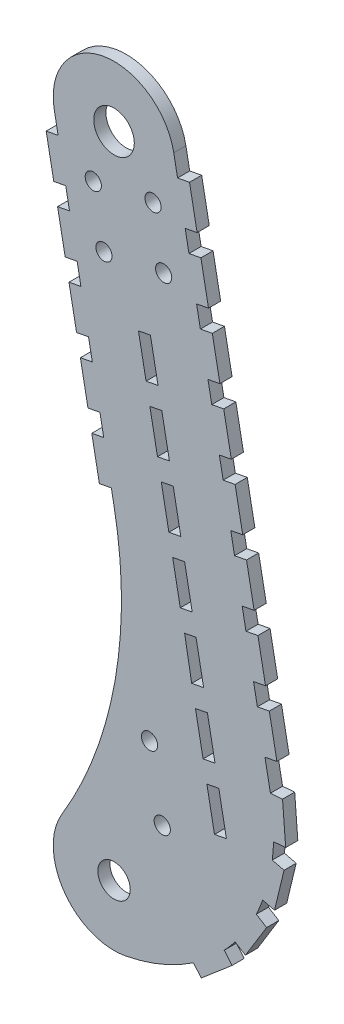
SolidWorks part; units mm, degrees
material "Thornel Mat VMA"
ref_plane "前视基准面" through (0, 0, 0) normal (0, 0, 1) x (1, 0, 0)
ref_plane "上视基准面" through (0, 0, 0) normal (0, 1, 0) x (1, 0, 0)
ref_plane "右视基准面" through (0, 0, 0) normal (1, 0, 0) x (0, 0, -1)
sketch "草图1" plane through (0, 0, 0) normal (0, 0, 1) x (1, 0, 0)
  line L0 (0, -55) -> (0, 55) construction
  line L1 (55, 0) -> (-55, 0) construction
  line L3 (-14.734, 77.1875) -> (0, 0)
  line L7 (38.5769, -42.0946) -> (14.734, 82.8125)
  circle A0 centre (0, 80) radius 4
  circle A1 centre (0, -80) radius 4
  arc A2 (14.734, 82.8125) -> (-14.734, 77.1875) centre (0, 80) ccw
  arc A3 (-12.8597, -72.278) -> (2.8125, -94.734) centre (0, -80) ccw
  arc A4 (2.8125, -94.734) -> (38.5769, -42.0946) centre (-5.625, -50.5321) ccw
  arc A5 (-12.8597, -72.278) -> (0, 0) centre (-101.0914, -19.2969) ccw
  dimension "D1" = 80
  dimension "D2" = 8
extrude "凸台-拉伸1" add sketch "草图1" along normal blind 3
sketch "草图3" plane through (29.4679, 5.625, 0) normal (0.9823, 0.1875, 0) x (0, 0, -1)
  line L0 (-3, -48.5812) -> (-3, 78.5812) construction
  line L1 (-3, 73.5812) -> (0, 73.5812)
  line L2 (-3, 73.5812) -> (-3, 63.5812)
  line L3 (-3, 63.5812) -> (0, 63.5812)
  line L4 (0, 73.5812) -> (0, 63.5812)
  line L5 (0, 55) -> (0, -55) construction
  line L6 (-3, 78.5812) -> (0, 78.5812) construction
  line L7 (-3, 58.5812) -> (-3, 48.5812)
  line L8 (-3, 58.5812) -> (0, 58.5812)
  line L9 (0, 58.5812) -> (0, 48.5812)
  line L10 (-3, 48.5812) -> (0, 48.5812)
  line L11 (-3, 43.5812) -> (-3, 33.5812)
  line L12 (-3, 43.5812) -> (0, 43.5812)
  line L13 (0, 43.5812) -> (0, 33.5812)
  line L14 (-3, 33.5812) -> (0, 33.5812)
  line L15 (-3, 28.5812) -> (-3, 18.5812)
  line L16 (-3, 28.5812) -> (0, 28.5812)
  line L17 (0, 28.5812) -> (0, 18.5812)
  line L18 (-3, 18.5812) -> (0, 18.5812)
  line L19 (-3, 13.5812) -> (-3, 3.5812)
  line L20 (-3, 13.5812) -> (0, 13.5812)
  line L21 (0, 13.5812) -> (0, 3.5812)
  line L22 (-3, 3.5812) -> (0, 3.5812)
  line L23 (-3, -1.4188) -> (-3, -11.4188)
  line L24 (-3, -1.4188) -> (0, -1.4188)
  line L25 (0, -1.4188) -> (0, -11.4188)
  line L26 (-3, -11.4188) -> (0, -11.4188)
  line L27 (-3, -16.4188) -> (-3, -26.4188)
  line L28 (-3, -16.4188) -> (0, -16.4188)
  line L29 (0, -16.4188) -> (0, -26.4188)
  line L30 (-3, -26.4188) -> (0, -26.4188)
  line L31 (-3, -31.4188) -> (-3, -41.4188)
  line L32 (-3, -31.4188) -> (0, -31.4188)
  line L33 (0, -31.4188) -> (0, -41.4188)
  line L34 (-3, -41.4188) -> (0, -41.4188)
  dimension "D1" = 10
  dimension "D2" = 5
  dimension "D3" = 8
extrude "凸台-拉伸2" add sketch "草图3" along normal blind 3
sketch "草图5" plane through (0, 0, 3) normal (0, 0, 1) x (1, 0, 0)
  line L1 (39.349, -52.0617) -> (42.34, -51.8301)
  line L2 (42.34, -51.8301) -> (41.5679, -41.8629)
  line L3 (41.5679, -41.8629) -> (38.5769, -42.0946)
  line L4 (39.349, -52.0617) -> (35.8524, -52.0617)
  line L5 (35.8524, -52.0617) -> (38.5769, -42.0946)
  line L6 (0, 0) -> (-7.367, 38.5938)
  line L7 (-14.734, 77.1875) -> (0, 0) construction
  line L8 (39.0208, -56.1667) -> (31.0458, -56.5186)
  line L9 (31.0458, -56.5186) -> (36.6751, -65.8846)
  line L10 (41.9371, -56.8706) -> (39.0208, -56.1667)
  line L12 (36.6751, -65.8846) -> (39.5914, -66.5885)
  line L13 (39.5914, -66.5885) -> (41.9371, -56.8706)
  line L14 (35.0945, -69.6872) -> (30.758, -62.4722)
  line L15 (37.6505, -71.2579) -> (35.0945, -69.6872)
  line L17 (29.8606, -78.2047) -> (32.4166, -79.7753)
  line L18 (32.4166, -79.7753) -> (37.6505, -71.2579)
  line L19 (30.758, -62.4722) -> (29.8606, -78.2047)
  line L20 (29.1278, -83.6163) -> (27.1823, -81.3327)
  line L22 (19.5725, -87.8159) -> (21.518, -90.0995)
  line L23 (21.518, -90.0995) -> (29.1278, -83.6163)
  line L24 (27.1823, -81.3327) -> (19.5725, -65.4977)
  line L29 (19.5725, -65.4977) -> (19.5725, -87.8159)
  line L34 (17.2033, -92.7363) -> (16.0587, -89.9632) [skipped]
  line L36 (6.8179, -93.7776) -> (7.9625, -96.5506) [skipped]
  line L37 (7.9625, -96.5506) -> (17.2033, -92.7363) [skipped]
  line L39 (-6.923, -98.4971) -> (3.0442, -97.725) [skipped]
  line L40 (-7.1547, -95.5061) -> (-6.923, -98.4971) [skipped]
  line L41 (3.0442, -97.725) -> (2.8125, -94.734) [skipped]
  arc A0 (2.8125, -94.734) -> (38.5769, -42.0946) centre (-5.625, -50.5321) ccw construction
  point P48 (-5.625, -50.5321)
  arc M20 (2.8125, -94.734) -> (38.5769, -42.0946) centre (-5.625, -50.5321) ccw
  dimension "D1" = 6
extrude "凸台-拉伸3" add sketch "草图5" against normal blind 3 contours L12 L13 L10 M20 | L8 L9 M20 | L5 L4 M20 | L2 L3 L1 M20 | L14 L19 M20 | L17 L18 L15 M20 | L24 L29 M20 | L22 L23 L20 M20
sketch "草图6" plane through (0, 0, 0) normal (-0.9823, -0.1875, 0) x (0, 0, 1)
  line L0 (0, -55) -> (0, 55) construction
  line L1 (0, 73.5812) -> (3, 73.5812)
  line L2 (0, 73.5812) -> (0, 63.5812)
  line L3 (0, 63.5812) -> (3, 63.5812)
  line L4 (3, 73.5812) -> (3, 63.5812)
  line L5 (3, 78.5812) -> (0, 78.5812) construction
  line L6 (0, 58.5812) -> (0, 48.5812)
  line L7 (0, 58.5812) -> (3, 58.5812)
  line L8 (3, 58.5812) -> (3, 48.5812)
  line L9 (0, 48.5812) -> (3, 48.5812)
  line L10 (0, 43.5812) -> (0, 33.5812)
  line L11 (0, 43.5812) -> (3, 43.5812)
  line L12 (3, 43.5812) -> (3, 33.5812)
  line L13 (0, 33.5812) -> (3, 33.5812)
  line L14 (0, 28.5812) -> (0, 18.5812)
  line L15 (0, 28.5812) -> (3, 28.5812)
  line L16 (3, 28.5812) -> (3, 18.5812)
  line L17 (0, 18.5812) -> (3, 18.5812)
  line L18 (0, 13.5812) -> (0, 3.5812)
  line L19 (0, 13.5812) -> (3, 13.5812)
  line L20 (3, 13.5812) -> (3, 3.5812)
  line L21 (0, 3.5812) -> (3, 3.5812)
  dimension "D1" = 3
  dimension "D2" = 10
  dimension "D3" = 5
  dimension "D4" = 5
extrude "凸台-拉伸4" add sketch "草图6" along normal blind 3
sketch "草图9" plane through (0, 0, 3) normal (0, 0, 1) x (1, 0, 0)
  circle A1 centre (11.891, -62.2941) radius 2
  circle A3 centre (8.7504, -45.8411) radius 2
extrude "切除-拉伸1" cut sketch "草图9" against normal blind 3
sketch "草图10" plane through (0, 0, 3) normal (0, 0, 1) x (1, 0, 0)
  line L5 (7.5, 40.7094) -> (8.9734, 40.9907)
  line L6 (8.9734, 40.9907) -> (10.8484, 31.168)
  line L7 (10.8484, 31.168) -> (7.9016, 30.6055)
  line L8 (7.9016, 30.6055) -> (6.0266, 40.4282)
  line L9 (6.0266, 40.4282) -> (7.5, 40.7094)
  line L13 (10.3125, 25.9754) -> (11.7859, 26.2567)
  line L14 (11.7859, 26.2567) -> (13.6609, 16.4341)
  line L15 (13.6609, 16.4341) -> (10.7141, 15.8716)
  line L16 (10.7141, 15.8716) -> (8.8391, 25.6942)
  line L17 (8.8391, 25.6942) -> (10.3125, 25.9754)
  line L19 (13.125, 11.2415) -> (14.5984, 11.5227)
  line L20 (14.5984, 11.5227) -> (16.4734, 1.7001)
  line L21 (16.4734, 1.7001) -> (13.5266, 1.1376)
  line L22 (13.5266, 1.1376) -> (11.6516, 10.9602)
  line L23 (11.6516, 10.9602) -> (13.125, 11.2415)
  line L25 (15.9375, -3.4925) -> (17.4109, -3.2112)
  line L26 (17.4109, -3.2112) -> (19.2859, -13.0339)
  line L27 (19.2859, -13.0339) -> (16.3391, -13.5964)
  line L28 (16.3391, -13.5964) -> (14.4641, -3.7737)
  line L29 (14.4641, -3.7737) -> (15.9375, -3.4925)
  line L31 (18.75, -18.2265) -> (20.2234, -17.9452)
  line L32 (20.2234, -17.9452) -> (22.0984, -27.7679)
  line L33 (22.0984, -27.7679) -> (19.1516, -28.3304)
  line L34 (19.1516, -28.3304) -> (17.4109, -18.4821)
  line L35 (17.4109, -18.4821) -> (18.75, -18.2265)
  line L37 (21.5625, -32.9604) -> (23.0359, -32.6792)
  line L38 (23.0359, -32.6792) -> (24.9109, -42.5018)
  line L39 (24.9109, -42.5018) -> (21.9641, -43.0643)
  line L40 (21.9641, -43.0643) -> (20.0891, -33.2417)
  line L41 (20.0891, -33.2417) -> (21.5625, -32.9604)
  line L43 (24.375, -47.6944) -> (25.8484, -47.4131)
  line L44 (25.8484, -47.4131) -> (27.7234, -57.2358)
  line L45 (27.7234, -57.2358) -> (24.7766, -57.7983)
  line L46 (24.7766, -57.7983) -> (22.9016, -47.9756)
  line L47 (22.9016, -47.9756) -> (24.375, -47.6944)
  dimension "D1" = 1.5
  dimension "D5" = 10
  dimension "D2" = 10
  dimension "D4" = 1.5
extrude "切除-拉伸2" cut sketch "草图10" against normal blind 3
sketch "草图11" plane through (0, 0, 3) normal (0, 0, 1) x (1, 0, 0)
  circle A0 centre (9.617, 69.6191) radius 2
  circle A1 centre (12.242, 55.8674) radius 2
  circle A2 centre (-5.117, 66.8066) radius 2
  circle A3 centre (-2.492, 53.0549) radius 2
extrude "切除-拉伸3" cut sketch "草图11" against normal blind 10
sketch "草图12" plane through (0, 0, 3) normal (0, 0, 1) x (1, 0, 0)
  circle A0 centre (0, 80) radius 5
extrude "切除-拉伸4" cut sketch "草图12" against normal blind 10
